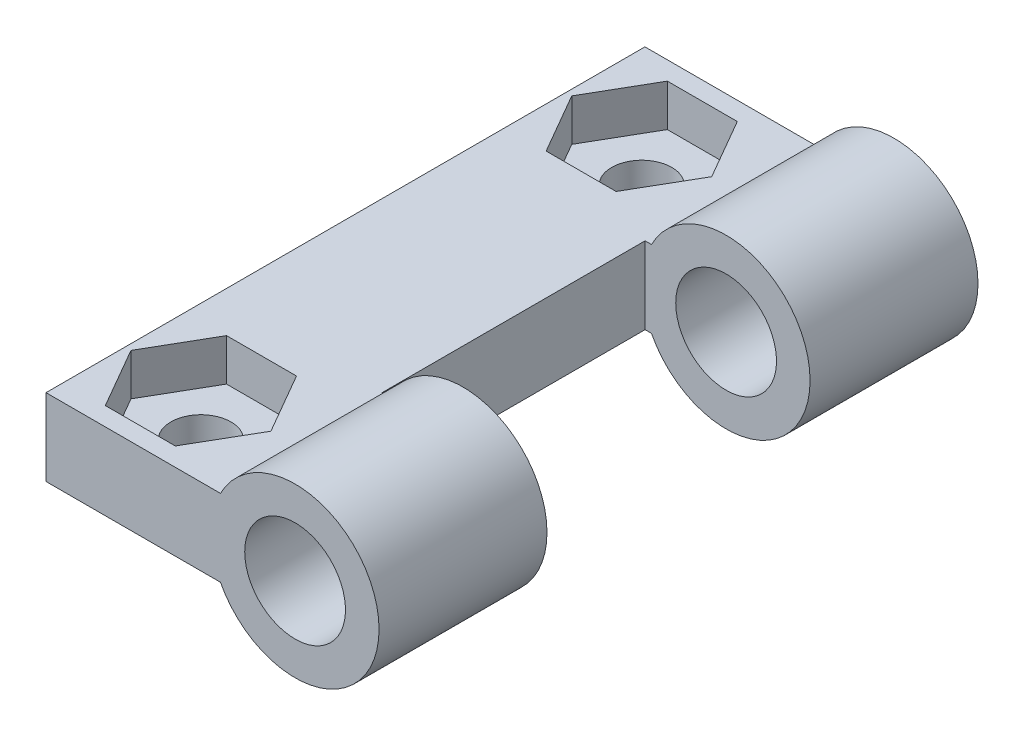
SolidWorks part; units mm, degrees
ref_plane "前视基准面" through (0, 0, 0) normal (0, 0, 1) x (1, 0, 0)
ref_plane "上视基准面" through (0, 0, 0) normal (0, 1, 0) x (1, 0, 0)
ref_plane "右视基准面" through (0, 0, 0) normal (1, 0, 0) x (0, 0, -1)
sketch "草图1" plane through (0, 0, 0) normal (0, 1, 0) x (1, 0, 0)
  line L1 (0, 0) -> (17.8, 0)
  line L2 (0, 0) -> (0, -42.8)
  line L3 (0, -42.8) -> (17.8, -42.8)
  line L4 (17.8, 0) -> (17.8, -42.8)
  dimension "D1" = 42.8
  dimension "D2" = 17.8
extrude "凸台-拉伸1" add sketch "草图1" along normal blind 5.5
sketch "草图2" plane through (0, 0, 0) normal (0, 0, -1) x (-1, 0, 0)
  line L0 (-17.8, 5.5) -> (-17.8, 0) construction
  circle A0 centre (-17.8, 2.75) radius 6
extrude "凸台-拉伸2" add sketch "草图2" against normal blind 12
sketch "草图3" plane through (0, 0, 42.8) normal (0, 0, 1) x (1, 0, 0)
  line L0 (17.8, 5.5) -> (17.8, 0) construction
  circle A0 centre (17.8, 2.75) radius 6
extrude "凸台-拉伸3" add sketch "草图3" against normal blind 12
sketch "草图4" plane through (0, 0, 0) normal (0, 0, -1) x (-1, 0, 0)
  circle A0 centre (-17.8, 2.75) radius 3.6002
  arc A1 (-12.4673, 5.5) -> (-12.4673, 0) centre (-17.8, 2.75) ccw construction
  dimension "D1" = 0
extrude "切除-拉伸1" cut sketch "草图4" against normal blind 51
ref_plane "基准面4" through (0, 0, 30.8) normal (0, 0, -1) x (-1, 0, 0)
sketch "草图5" plane through (0, 0, 30.8) normal (0, 0, -1) x (-1, 0, 0)
  line L1 (-12.0087, 8.0041) -> (-17.9515, 8.0041)
  line L2 (-12.0087, 8.0041) -> (-12.0087, -2.693)
  line L3 (-12.0087, -2.693) -> (-17.9515, -2.693)
  line L4 (-17.9515, 8.0041) -> (-17.9515, -2.693)
extrude "切除-拉伸2" cut sketch "草图5" along normal up to surface (18.8 mm away) up to face at (18.286, 2.75, 12)
sketch "草图6" plane through (0, 5.5, 0) normal (0, 1, 0) x (1, 0, 0)
  line L0 (0, -42.8) -> (12.4673, -42.8) construction
  circle A0 centre (5.4204, -5.65) radius 2.15
  circle A1 centre (5.4204, -37.15) radius 2.15
  point P4 (5.4204, -17.5066)
  dimension "D1" = 4.3
  dimension "D2" = 31.5
  dimension "D3" = 5.65
extrude "切除-拉伸3" cut sketch "草图6" against normal blind 10
sketch "草图7" plane through (0, 5.5, 0) normal (0, 1, 0) x (1, 0, 0)
  line L16 (2.9204, -1.3199) -> (7.9204, -1.3199)
  line L17 (7.9204, -1.3199) -> (10.4204, -5.65)
  line L18 (10.4204, -5.65) -> (7.9204, -9.9801)
  line L19 (7.9204, -9.9801) -> (2.9204, -9.9801)
  line L20 (2.9204, -9.9801) -> (0.4204, -5.65)
  line L21 (0.4204, -5.65) -> (2.9204, -1.3199)
  line L22 (7.9204, -1.3199) -> (2.9204, -9.9801) construction
  line L23 (2.9204, -1.3199) -> (7.9204, -9.9801) construction
  line L24 (0.4204, -5.65) -> (10.4204, -5.65) construction
  line L25 (0.4204, -37.15) -> (2.9204, -32.8199)
  line L26 (2.9204, -32.8199) -> (7.9204, -32.8199)
  line L27 (7.9204, -32.8199) -> (10.4204, -37.15)
  line L28 (10.4204, -37.15) -> (7.9204, -41.4801)
  line L29 (7.9204, -41.4801) -> (2.9204, -41.4801)
  line L30 (2.9204, -41.4801) -> (0.4204, -37.15)
  circle A1 centre (5.4204, -5.65) radius 2.15 construction
  dimension "D2" = 5
  dimension "D3" = 5
  dimension "D1" = 5
  dimension "D4" = 2
extrude "切除-拉伸4" cut sketch "草图7" against normal blind 3
